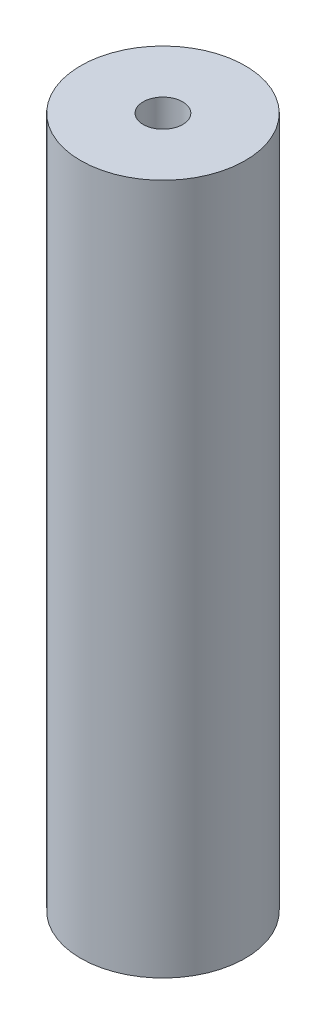
SolidWorks part; units mm, degrees
ref_plane "Front Plane" through (0, 0, 0) normal (0, 0, 1) x (1, 0, 0)
ref_plane "Top Plane" through (0, 0, 0) normal (0, 1, 0) x (1, 0, 0)
ref_plane "Right Plane" through (0, 0, 0) normal (1, 0, 0) x (0, 0, -1)
sketch "Sketch1" plane through (0, 0, 0) normal (0, 1, 0) x (1, 0, 0)
  circle A0 centre (0, 0) radius 12.5
  circle A1 centre (0, 0) radius 3
  dimension "D1" = 25
  dimension "D2" = 6
extrude "Boss-Extrude1" add sketch "Sketch1" along normal blind 105
